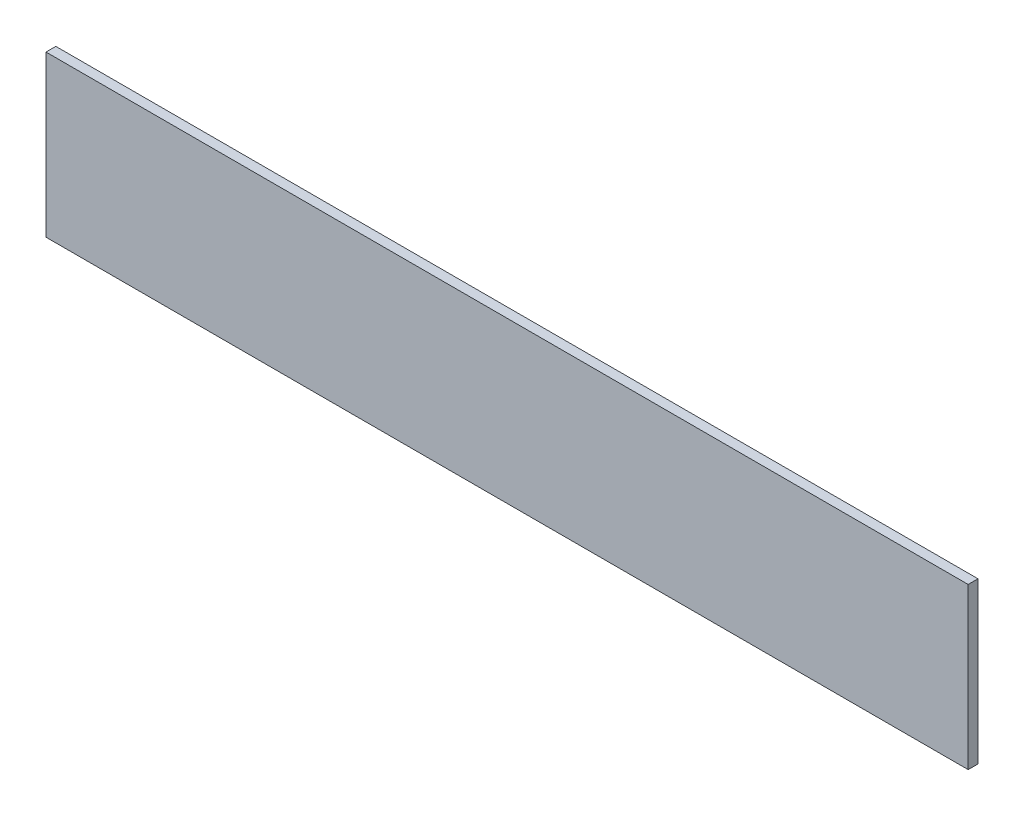
SolidWorks part; units mm, degrees
material "6061 Alloy"
ref_plane "Front Plane" through (0, 0, 0) normal (0, 0, 1) x (1, 0, 0)
ref_plane "Top Plane" through (0, 0, 0) normal (0, 1, 0) x (1, 0, 0)
ref_plane "Right Plane" through (0, 0, 0) normal (1, 0, 0) x (0, 0, -1)
sketch "Sketch1" plane through (0, 0, 0) normal (0, 0, 1) x (1, 0, 0)
  line L1 (-227.6475, 59.7694) -> (-8.5725, 59.7694)
  line L2 (-227.6475, 59.7694) -> (-227.6475, 21.6694)
  line L3 (-227.6475, 21.6694) -> (-8.5725, 21.6694)
  line L4 (-8.5725, 59.7694) -> (-8.5725, 21.6694)
  dimension "D1" = 38.1
  dimension "D2" = 219.075
extrude "Boss-Extrude1" add sketch "Sketch1" along normal blind 2.3368
